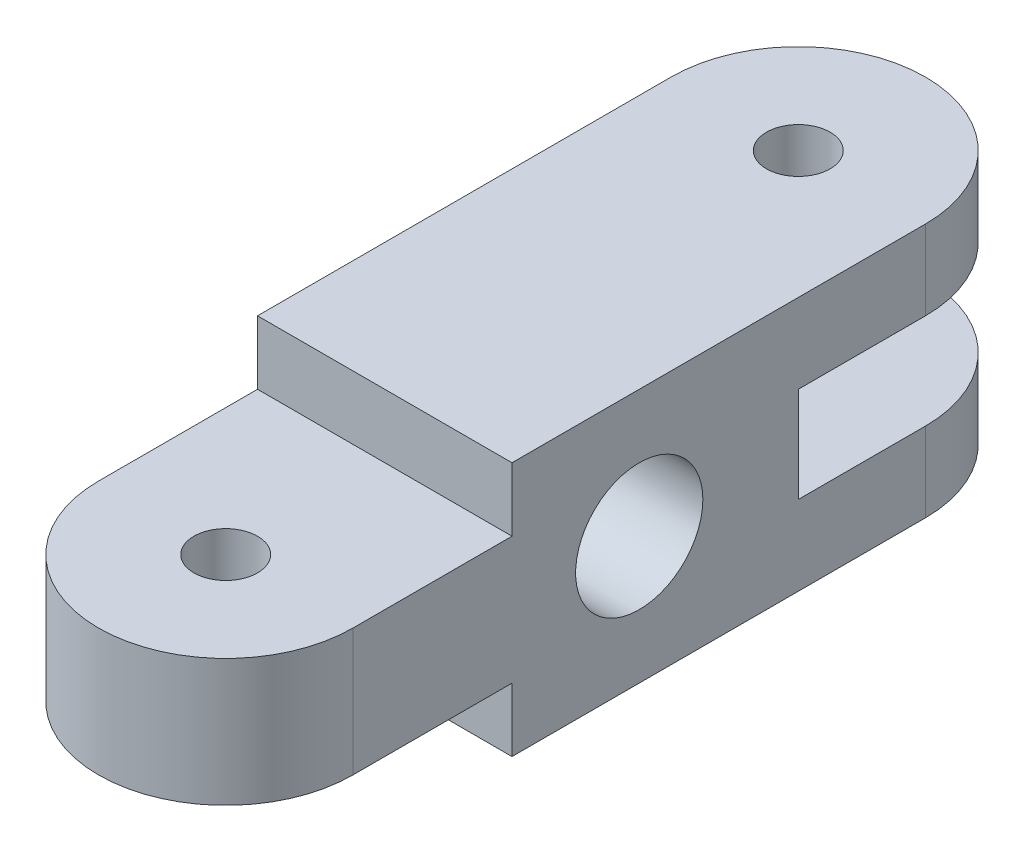
SolidWorks part; units mm, degrees
material "6061-T6 (SS)"
ref_plane "Front" through (0, 0, 0) normal (0, 0, 1) x (1, 0, 0)
ref_plane "Top" through (0, 0, 0) normal (0, 1, 0) x (1, 0, 0)
ref_plane "Right" through (0, 0, 0) normal (1, 0, 0) x (0, 0, -1)
sketch "Sketch2" plane through (0, 0, 0) normal (0, 0, 1) x (1, 0, 0)
  line L1 (-12.7, -12.7) -> (12.7, -12.7)
  line L2 (-12.7, -12.7) -> (-12.7, 12.7)
  line L3 (-12.7, 12.7) -> (12.7, 12.7)
  line L4 (12.7, -12.7) -> (12.7, 12.7)
  line L5 (-12.7, -12.7) -> (12.7, 12.7) construction
  line L6 (-12.7, 12.7) -> (12.7, -12.7) construction
  point P0 (0, 0)
  dimension "D1" = 25.4
  dimension "D2" = 25.4
extrude "Boss-Extrude1" add sketch "Sketch2" along normal mid plane 82.55
sketch "Sketch3" plane through (12.7, 0, 0) normal (1, 0, 0) x (0, 0, -1)
  line L0 (41.275, -12.7) -> (41.275, 12.7) construction
  line L1 (-41.275, 12.7) -> (-12.7, 12.7)
  line L2 (-41.275, 12.7) -> (-41.275, 6.35)
  line L3 (-41.275, 6.35) -> (-12.7, 6.35)
  line L4 (-12.7, 12.7) -> (-12.7, 6.35)
  line L5 (-41.275, -12.7) -> (-12.7, -12.7)
  line L6 (-41.275, -12.7) -> (-41.275, -6.35)
  line L7 (-41.275, -6.35) -> (-12.7, -6.35)
  line L8 (-12.7, -12.7) -> (-12.7, -6.35)
  line L9 (41.275, 4.7625) -> (15.875, 4.7625)
  line L10 (41.275, 4.7625) -> (41.275, -4.7625)
  line L11 (41.275, -4.7625) -> (15.875, -4.7625)
  line L12 (15.875, 4.7625) -> (15.875, -4.7625)
  circle A0 centre (0, 0) radius 6.35
  point P20 (15.875, 0)
  dimension "D1" = 12.7
  dimension "D2" = 6.35
  dimension "D3" = 6.35
  dimension "D4" = 28.575
  dimension "D5" = 28.575
  dimension "D6" = 25.4
  dimension "D7" = 9.525
extrude "Cut-Extrude1" cut sketch "Sketch3" against normal through all
sketch "Sketch4" plane through (0, 12.7, 0) normal (0, 1, 0) x (1, 0, 0)
  line L0 (-12.7, -41.275) -> (12.7, -41.275) construction
  line L1 (12.7, 41.275) -> (-12.7, 41.275) construction
  line L2 (-12.7, 28.575) -> (-12.7, 47.625)
  line L3 (-12.7, 47.625) -> (12.7, 47.625)
  line L4 (12.7, 47.625) -> (12.7, 28.575)
  line L5 (-12.7, -28.575) -> (-12.7, -47.625)
  line L6 (-12.7, -47.625) -> (12.7, -47.625)
  line L7 (12.7, -47.625) -> (12.7, -28.575)
  line L8 (-12.7, -41.275) -> (-12.7, -12.7) construction
  line L9 (-12.7, -12.7) -> (-12.7, 41.275) construction
  circle A0 centre (0, 28.575) radius 3.175
  circle A1 centre (0, -28.575) radius 3.175
  arc A2 (-12.7, -28.575) -> (12.7, -28.575) centre (0, -28.575) ccw
  arc A3 (12.7, 28.575) -> (-12.7, 28.575) centre (0, 28.575) ccw
  dimension "D1" = 6.35
  dimension "D2" = 6.35
  dimension "D3" = 12.7
  dimension "D4" = 12.7
  dimension "D5" = 19.05
  dimension "D6" = 19.05
extrude "Cut-Extrude2" cut sketch "Sketch4" against normal through all
